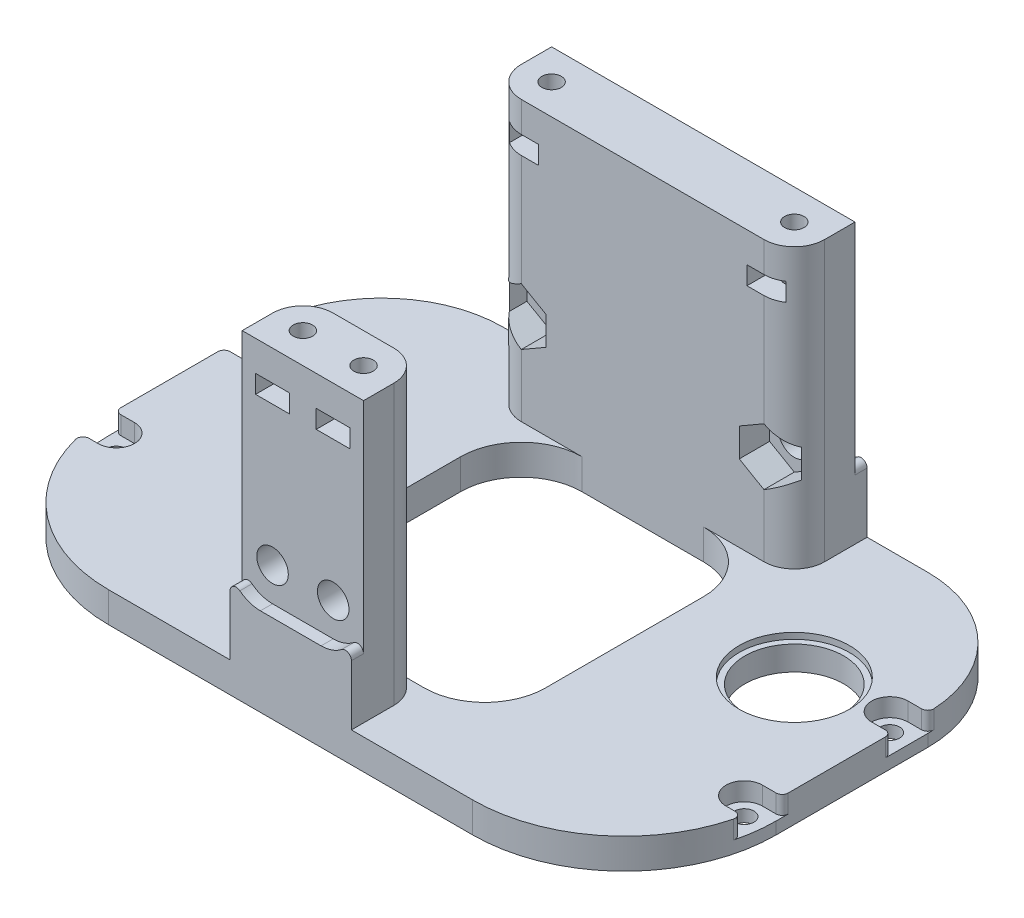
SolidWorks part; units mm, degrees
ref_plane "Alzado" through (0, 0, 0) normal (0, 0, 1) x (1, 0, 0)
ref_plane "Planta" through (0, 0, 0) normal (0, 1, 0) x (1, 0, 0)
ref_plane "Vista lateral" through (0, 0, 0) normal (1, 0, 0) x (0, 0, -1)
sketch "Croquis1" plane through (0, 0, 0) normal (0, 1, 0) x (1, 0, 0)
  line L4 (-60.5, 0) -> (60.5, 0) construction
  line L5 (-30, -35) -> (30, -35)
  line L10 (-55, -10) -> (-55, 15)
  line L11 (-35, 35) -> (35, 35)
  line L12 (55, -10) -> (55, 15)
  line L13 (-55, -35) -> (55, 35) construction
  line L14 (-55, 35) -> (55, -35) construction
  line L15 (-10, -23) -> (10, -23)
  line L16 (-20, -13) -> (-20, 13)
  line L17 (-10, 23) -> (10, 23)
  line L18 (20, -13) -> (20, 13)
  line L19 (-20, -23) -> (20, 23) construction
  line L20 (-20, 23) -> (20, -23) construction
  line L21 (0, -38.5) -> (0, 38.5) construction
  arc A14 (35, 35) -> (55, 15) centre (35, 15) cw
  arc A15 (-35, 35) -> (-55, 15) centre (-35, 15) ccw
  arc A16 (30, -35) -> (55, -10) centre (30, -10) ccw
  arc A17 (-30, -35) -> (-55, -10) centre (-30, -10) cw
  arc A18 (-10, -23) -> (-20, -13) centre (-10, -13) cw
  arc A19 (10, -23) -> (20, -13) centre (10, -13) ccw
  arc A20 (10, 23) -> (20, 13) centre (10, 13) cw
  arc A21 (-20, 13) -> (-10, 23) centre (-10, 13) cw
  circle A22 centre (39, 9) radius 8.15
  circle A23 centre (51.75, 12) radius 1.6
  circle A24 centre (51.75, -12) radius 1.6
  circle A25 centre (-51.75, -12) radius 1.6
  circle A26 centre (-51.75, 12) radius 1.6
  circle A27 centre (-39, 9) radius 8.15
  point P0 (0, 0)
  point P17 (0, 0)
  point P38 (55, 2.5)
  dimension "D3" = 20
  dimension "D4" = 25
  dimension "D7" = 10
  dimension "D8" = 3.2
  dimension "D9" = 16.3
  dimension "D1" = 110
  dimension "D2" = 70
  dimension "D5" = 46
  dimension "D6" = 40
  dimension "D10" = 9.5
  dimension "D11" = 3.25
  dimension "D12" = 16
  dimension "D13" = 6.5
extrude "Saliente-Extruir1" add sketch "Croquis1" along normal blind 5
sketch "Croquis2" plane through (0, 5, 0) normal (0, 1, 0) x (1, 0, 0)
  line L0 (0, -2.75) -> (0, 2.75) construction
  circle A0 centre (39, 9) radius 9.1
  circle A1 centre (-39, 9) radius 9.1
  dimension "D1" = 18.2
extrude "Cortar-Extruir1" cut sketch "Croquis2" against normal blind 1
sketch "Croquis3" plane through (0, 5, 0) normal (0, 1, 0) x (1, 0, 0)
  line L0 (51.75, 15) -> (55, 15)
  line L1 (51.75, 9) -> (55, 9)
  line L2 (55, -10) -> (55, 15) construction
  line L3 (55, 15) -> (55, 9)
  line L4 (-2.75, 0) -> (2.75, 0) construction
  line L5 (51.75, -15) -> (55, -15)
  line L6 (51.75, -9) -> (55, -9)
  line L7 (55, -15) -> (55, -9)
  line L8 (0, -2.75) -> (0, 2.75) construction
  line L9 (-51.75, -9) -> (-55, -9)
  line L10 (-55, -15) -> (-55, -9)
  line L11 (-51.75, -15) -> (-55, -15)
  line L12 (-51.75, 15) -> (-55, 15)
  line L13 (-51.75, 9) -> (-55, 9)
  line L14 (-55, 15) -> (-55, 9)
  arc A0 (51.75, 15) -> (51.75, 9) centre (51.75, 12) ccw
  arc A1 (51.75, -15) -> (51.75, -9) centre (51.75, -12) cw
  arc A2 (-51.75, -15) -> (-51.75, -9) centre (-51.75, -12) ccw
  arc A3 (-51.75, 15) -> (-51.75, 9) centre (-51.75, 12) cw
  dimension "D1" = 6
extrude "Cortar-Extruir2" cut sketch "Croquis3" against normal blind 3
fillet "Redondeo1" radius 1 8 edges at (54.4949, 3.5, 15) (55, 3.5, 9) (55, 3.5, -9) (55, 3.5, -15) (-54.4949, 3.5, 15) (-55, 3.5, 9) (-55, 3.5, -9) (-55, 3.5, -15)
sketch "Croquis4" plane through (0, 5, 0) normal (0, 1, 0) x (1, 0, 0)
  line L0 (35, 35) -> (-35, 35) construction
  line L1 (-25, 35) -> (25, 35)
  line L2 (-25, 35) -> (-25, 28)
  line L3 (-20, 23) -> (20, 23)
  line L4 (25, 35) -> (25, 28)
  line L5 (10, 23) -> (-10, 23) construction
  line L6 (0, -2.75) -> (0, 2.75) construction
  arc A0 (-25, 28) -> (-20, 23) centre (-20, 28) ccw
  arc A1 (20, 23) -> (25, 28) centre (20, 28) ccw
  point P9 (0, 23)
  dimension "D2" = 5
  dimension "D3" = 5
  dimension "D1" = 50
extrude "Saliente-Extruir2" add sketch "Croquis4" along normal blind 46
sketch "Croquis5" plane through (0, 0, -35) normal (0, 0, -1) x (-1, 0, 0)
  line L1 (-25, 51) -> (25, 51)
  line L3 (-20, 14.5) -> (20, 14.5)
  line L4 (25, 51) -> (25, 17.7087)
  line L5 (-25, 51) -> (-25, 17.7087)
  line L6 (-25, 51) -> (-25, 5) construction
  line L7 (0, 28.05) -> (0, -28.05) construction
  arc A0 (-25, 17.7087) -> (-20, 14.5) centre (-20, 20) ccw
  arc A1 (25, 17.7087) -> (20, 14.5) centre (20, 20) cw
  dimension "D2" = 11
  dimension "D1" = 36.5
  dimension "D3" = 5
extrude "Cortar-Extruir3" cut sketch "Croquis5" against normal blind 2
sketch "Croquis6" plane through (0, 0, -33) normal (0, 0, -1) x (-1, 0, 0)
  line L0 (-25, 51) -> (-25, 17.7087) construction
  line L1 (-22.8, 46) -> (-17.2, 46)
  line L2 (-22.8, 46) -> (-22.8, 43)
  line L3 (-22.8, 43) -> (-17.2, 43)
  line L4 (-17.2, 46) -> (-17.2, 43)
  line L5 (0, 28.05) -> (0, -28.05) construction
  line L6 (22.8, 43) -> (17.2, 43)
  line L7 (17.2, 46) -> (17.2, 43)
  line L8 (22.8, 46) -> (17.2, 46)
  line L9 (22.8, 46) -> (22.8, 43)
  circle A0 centre (-20, 20) radius 2.6
  circle A1 centre (20, 20) radius 2.6
  dimension "D1" = 5.2
  dimension "D2" = 5.6
  dimension "D3" = 3
  dimension "D4" = 5
  dimension "D5" = 2.2
extrude "Cortar-Extruir4" cut sketch "Croquis6" against normal up to surface (10 mm away) up to face at (0, 15.25, -23)
sketch "Croquis7" plane through (0, 0, -23) normal (0, 0, 1) x (1, 0, 0)
  line L1 (-20, 24.7) -> (-24.0703, 22.35)
  line L2 (-24.0703, 22.35) -> (-24.0703, 17.65)
  line L3 (-24.0703, 17.65) -> (-20, 15.3)
  line L4 (-20, 15.3) -> (-15.9297, 17.65)
  line L5 (-15.9297, 17.65) -> (-15.9297, 22.35)
  line L6 (-15.9297, 22.35) -> (-20, 24.7)
  line L7 (-20, 43) -> (-20, 22.6) construction
  line L8 (0, -28.05) -> (0, 28.05) construction
  line L9 (15.9297, 22.35) -> (20, 24.7)
  line L10 (15.9297, 17.65) -> (15.9297, 22.35)
  line L11 (20, 15.3) -> (15.9297, 17.65)
  line L12 (24.0703, 17.65) -> (20, 15.3)
  line L13 (24.0703, 22.35) -> (24.0703, 17.65)
  line L14 (20, 24.7) -> (24.0703, 22.35)
  circle A0 centre (-20, 20) radius 4.0703 construction
  dimension "D1" = 4.7
extrude "Cortar-Extruir5" cut sketch "Croquis7" against normal blind 5
sketch "Croquis8" plane through (0, 5, 0) normal (0, 1, 0) x (1, 0, 0)
  line L0 (0, -28.05) -> (0, 28.05) construction
  line L1 (-10, -35) -> (10, -35)
  line L2 (-10, -35) -> (-10, -28)
  line L3 (-5, -23) -> (5, -23)
  line L4 (10, -35) -> (10, -28)
  line L8 (-30, -35) -> (30, -35) construction
  line L9 (-10, -23) -> (10, -23) construction
  arc A0 (-10, -28) -> (-5, -23) centre (-5, -28) cw
  arc A1 (5, -23) -> (10, -28) centre (5, -28) cw
  point P18 (0, -35)
  dimension "D2" = 5
  dimension "D3" = 5
  dimension "D1" = 20
extrude "Saliente-Extruir3" add sketch "Croquis8" along normal blind 46
sketch "Croquis9" plane through (0, 0, 35) normal (0, 0, 1) x (1, 0, 0)
  line L0 (10, 51) -> (10, 17.7087)
  line L1 (-10, 51) -> (10, 51)
  line L3 (-5, 14.5) -> (5, 14.5)
  line L5 (-10, 51) -> (-10, 17.7087)
  line L6 (-10, 51) -> (-10, 5) construction
  line L7 (0, -28.05) -> (0, 28.05) construction
  arc A0 (-10, 17.7087) -> (-5, 14.5) centre (-5, 20) ccw
  arc A1 (10, 17.7087) -> (5, 14.5) centre (5, 20) cw
  line M12 (10, 5) -> (10, 51)
  line M13 (10, 51) -> (-10, 51)
  line M14 (-10, 51) -> (-10, 5)
  dimension "D2" = 11
  dimension "D1" = 36.5
  dimension "D3" = 5
  dimension "D4" = 5.5
extrude "Cortar-Extruir6" cut sketch "Croquis9" against normal blind 2 contours A1 A0 L3 M12 M13 M14
sketch "Croquis10" plane through (0, 0, 33) normal (0, 0, 1) x (1, 0, 0)
  line L0 (10, 51) -> (-10, 51) construction
  line L1 (-7.8, 46) -> (-2.2, 46)
  line L2 (-7.8, 46) -> (-7.8, 43)
  line L3 (-7.8, 43) -> (-2.2, 43)
  line L4 (-2.2, 46) -> (-2.2, 43)
  line L5 (-10, 51) -> (-10, 17.7087) construction
  line L6 (0, -28.05) -> (0, 28.05) construction
  line L7 (7.8, 43) -> (2.2, 43)
  line L8 (2.2, 46) -> (2.2, 43)
  line L9 (7.8, 46) -> (2.2, 46)
  line L10 (7.8, 46) -> (7.8, 43)
  circle A0 centre (-5, 20) radius 2.6
  circle A1 centre (5, 20) radius 2.6
  dimension "D1" = 5.2
  dimension "D2" = 3
  dimension "D3" = 5.6
  dimension "D4" = 5
  dimension "D5" = 2.2
extrude "Cortar-Extruir7" cut sketch "Croquis10" against normal up to surface (10 mm away) up to face at (0, 15.25, 23)
sketch "Croquis11" plane through (0, 51, 0) normal (0, 1, 0) x (1, 0, 0)
  line L0 (10, -33) -> (-10, -33) construction
  line L1 (-10, -28) -> (-10, -33) construction
  line L2 (-25, 33) -> (-25, 28) construction
  line L3 (-25, 33) -> (25, 33) construction
  line L4 (0, -28.05) -> (0, 28.05) construction
  circle A0 centre (-5, -28) radius 1.6
  circle A1 centre (-20, 28) radius 1.6
  circle A2 centre (5, -28) radius 1.6
  circle A3 centre (20, 28) radius 1.6
  dimension "D1" = 3.2
  dimension "D4" = 3.2
  dimension "D2" = 5
  dimension "D3" = 5
  dimension "D5" = 5
  dimension "D6" = 5
extrude "Cortar-Extruir8" cut sketch "Croquis11" against normal blind 21
fillet "Redondeo2" radius 1 4 edges at (-25, 17.7087, -34) (25, 17.7087, -34) (10, 17.7087, 34) (-10, 17.7087, 34)
